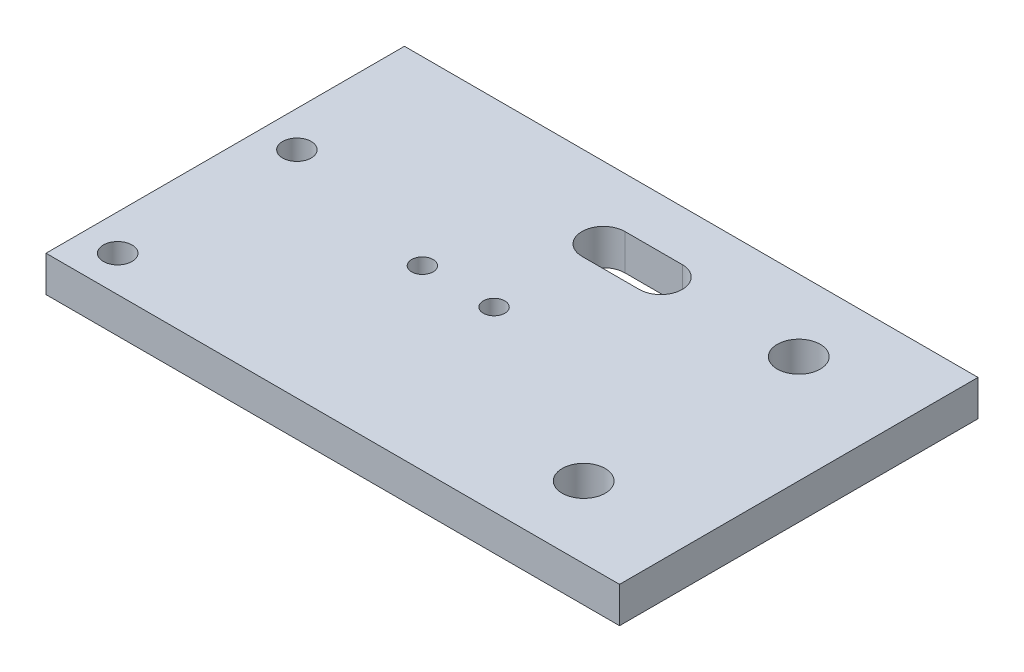
SolidWorks part; units mm, degrees
ref_plane "Front Plane" through (0, 0, 0) normal (0, 0, 1) x (1, 0, 0)
ref_plane "Top Plane" through (0, 0, 0) normal (0, 1, 0) x (1, 0, 0)
ref_plane "Right Plane" through (0, 0, 0) normal (1, 0, 0) x (0, 0, -1)
sketch "Sketch1" plane through (0, 0, 0) normal (0, 1, 0) x (1, 0, 0)
  line L1 (0, 0) -> (80, 0)
  line L2 (0, 0) -> (0, 50)
  line L3 (0, 50) -> (80, 50)
  line L4 (80, 0) -> (80, 50)
  circle A0 centre (65, 10) radius 3
  circle A1 centre (65, 40) radius 3
  dimension "D3" = 6
  dimension "D6" = 6
  dimension "D1" = 50
  dimension "D2" = 80
  dimension "D4" = 15
  dimension "D5" = 10
  dimension "D7" = 10
extrude "Boss-Extrude1" add sketch "Sketch1" along normal blind 5
sketch "Sketch2" plane through (0, 5, 0) normal (0, 1, 0) x (1, 0, 0)
  line L0 (37.7527, 40) -> (45.7527, 40) construction
  line L1 (37.7527, 43) -> (45.7527, 43)
  line L2 (37.7527, 37) -> (45.7527, 37)
  line L3 (0, 0) -> (80, 0) construction
  circle A0 centre (37.7527, 24.7437) radius 1.5
  circle A1 centre (27.7527, 24.7437) radius 1.5
  circle A2 centre (5, 30) radius 2
  circle A3 centre (5, 5) radius 2
  arc A4 (37.7527, 43) -> (37.7527, 37) centre (37.7527, 40) ccw
  arc A5 (45.7527, 37) -> (45.7527, 43) centre (45.7527, 40) ccw
  point P15 (41.7527, 40)
  dimension "D2" = 3
  dimension "D1" = 8
  dimension "D3" = 40
extrude "Cut-Extrude1" cut sketch "Sketch2" against normal blind 5 contours L1 A5 L2 A4
sketch "Sketch4" plane through (0, 5, 0) normal (0, 1, 0) x (1, 0, 0)
  circle A0 centre (37.7527, 24.7437) radius 1.5
  circle A1 centre (27.7527, 24.7437) radius 1.5
  circle A2 centre (5, 30) radius 2
  circle A3 centre (5, 5) radius 2
extrude "Cut-Extrude2" cut sketch "Sketch4" against normal blind 10
